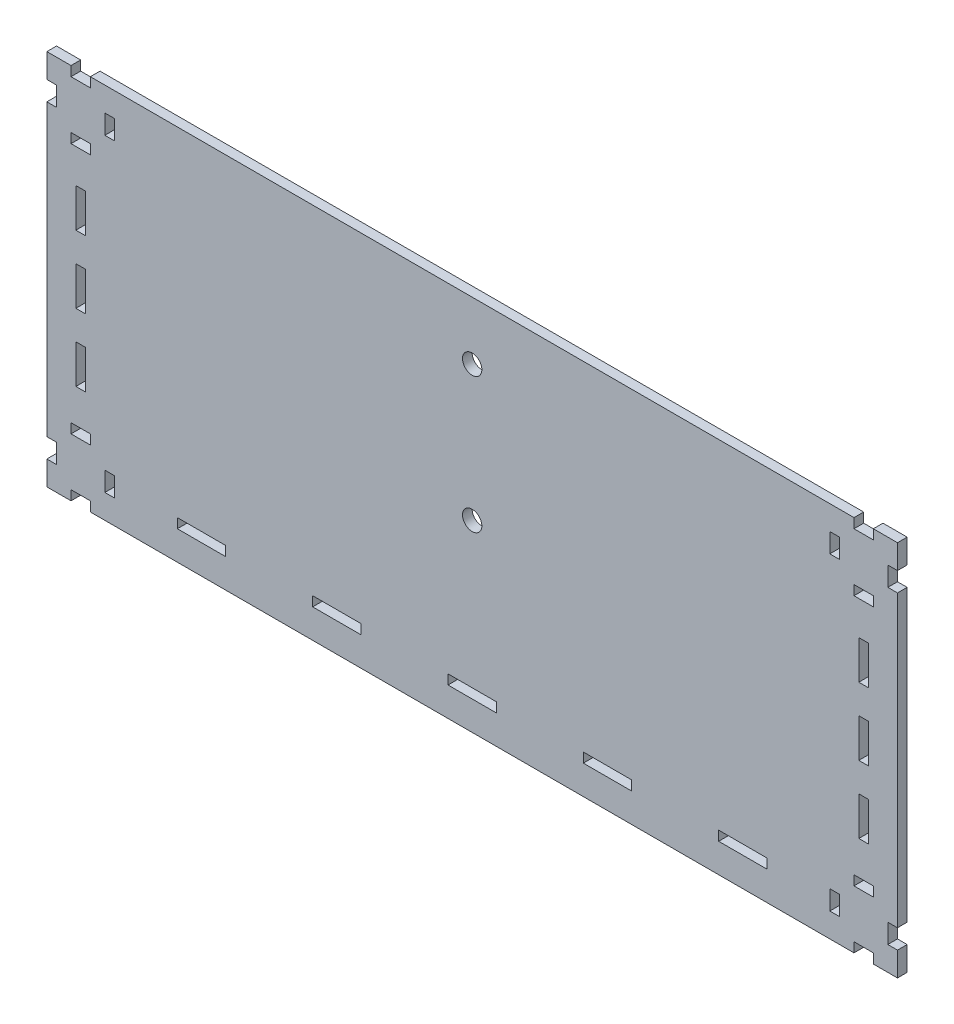
SolidWorks part; units mm, degrees
ref_plane "Front Plane" through (0, 0, 0) normal (0, 0, 1) x (1, 0, 0)
ref_plane "Top Plane" through (0, 0, 0) normal (0, 1, 0) x (1, 0, 0)
ref_plane "Right Plane" through (0, 0, 0) normal (1, 0, 0) x (0, 0, -1)
sketch "Sketch1" plane through (0, 0, 0) normal (0, 0, 1) x (1, 0, 0)
  line L0 (-225, 5) -> (-225, 67.9195) construction
  line L9 (0, 0) -> (-450, 0) construction
  line L10 (0, 0) -> (0, 200) construction
  line L11 (0, 200) -> (-17.5, 200) construction
  line L12 (-450, 0) -> (-450, 200) construction
  line L13 (-5, 5) -> (-17.5, 5)
  line L14 (-5, 5) -> (-5, 17.5)
  line L15 (-5, 200) -> (-17.5, 200)
  line L16 (-445, 5) -> (-445, 17.5)
  line L17 (-17.5, 35) -> (-27.5, 35)
  line L18 (-17.5, 35) -> (-17.5, 40)
  line L19 (-17.5, 40) -> (-27.5, 40)
  line L20 (-27.5, 35) -> (-27.5, 40)
  line L22 (-17.5, 5) -> (-17.5, 10)
  line L23 (-17.5, 10) -> (-27.5, 10)
  line L24 (-27.5, 5) -> (-27.5, 10)
  line L25 (-5, 17.5) -> (-10, 17.5)
  line L27 (-5, 27.5) -> (-10, 27.5)
  line L28 (-10, 17.5) -> (-10, 27.5)
  line L29 (-35.0003, 17.5) -> (-40, 17.5)
  line L30 (-35.0003, 17.5) -> (-35.0003, 27.5)
  line L31 (-35.0003, 27.5) -> (-40, 27.5)
  line L32 (-40, 17.5) -> (-40, 27.5)
  line L33 (-5, 102.5) -> (-45.4791, 102.5) construction
  line L34 (-410, 17.5) -> (-410, 27.5)
  line L35 (-414.9997, 27.5) -> (-410, 27.5)
  line L36 (-414.9997, 17.5) -> (-414.9997, 27.5)
  line L37 (-414.9997, 17.5) -> (-410, 17.5)
  line L38 (-440, 17.5) -> (-440, 27.5)
  line L39 (-445, 27.5) -> (-440, 27.5)
  line L41 (-445, 17.5) -> (-440, 17.5)
  line L42 (-422.5, 5) -> (-422.5, 10)
  line L43 (-432.5, 10) -> (-422.5, 10)
  line L44 (-432.5, 5) -> (-432.5, 10)
  line L46 (-422.5, 35) -> (-422.5, 40)
  line L47 (-432.5, 40) -> (-422.5, 40)
  line L48 (-432.5, 35) -> (-432.5, 40)
  line L49 (-432.5, 35) -> (-422.5, 35)
  line L50 (-432.5, 170) -> (-422.5, 170)
  line L51 (-432.5, 170) -> (-432.5, 165)
  line L52 (-432.5, 165) -> (-422.5, 165)
  line L53 (-422.5, 170) -> (-422.5, 165)
  line L55 (-432.5, 200) -> (-432.5, 195)
  line L56 (-432.5, 195) -> (-422.5, 195)
  line L57 (-422.5, 200) -> (-422.5, 195)
  line L58 (-445, 187.5) -> (-440, 187.5)
  line L60 (-445, 177.5) -> (-440, 177.5)
  line L61 (-440, 187.5) -> (-440, 177.5)
  line L62 (-414.9997, 187.5) -> (-410, 187.5)
  line L63 (-414.9997, 187.5) -> (-414.9997, 177.5)
  line L64 (-414.9997, 177.5) -> (-410, 177.5)
  line L65 (-410, 187.5) -> (-410, 177.5)
  line L66 (0, 205) -> (-450, 205) construction
  line L67 (-40, 187.5) -> (-40, 177.5)
  line L68 (-35.0003, 177.5) -> (-40, 177.5)
  line L69 (-35.0003, 187.5) -> (-35.0003, 177.5)
  line L70 (-35.0003, 187.5) -> (-40, 187.5)
  line L71 (-10, 187.5) -> (-10, 177.5)
  line L72 (-5, 177.5) -> (-10, 177.5)
  line L73 (-5, 187.5) -> (-10, 187.5)
  line L74 (-27.5, 200) -> (-27.5, 195)
  line L75 (-17.5, 195) -> (-27.5, 195)
  line L76 (-17.5, 200) -> (-17.5, 195)
  line L77 (-27.5, 170) -> (-27.5, 165)
  line L78 (-17.5, 165) -> (-27.5, 165)
  line L79 (-17.5, 170) -> (-17.5, 165)
  line L80 (-17.5, 170) -> (-27.5, 170)
  line L81 (-5, 187.5) -> (-5, 200)
  line L82 (-27.5, 200) -> (-422.5, 200) construction
  line L83 (-27.5, 200) -> (-422.5, 200)
  line L84 (-445, 187.5) -> (-445, 200)
  line L85 (-432.5, 200) -> (-450, 200) construction
  line L86 (-432.5, 200) -> (-445, 200)
  line L87 (-445, 27.5) -> (-445, 177.5)
  line L88 (-432.5, 5) -> (-445, 5)
  line L89 (-27.5, 5) -> (-422.5, 5)
  line L90 (-5, 27.5) -> (-5, 177.5)
  line L103 (-430, 57.5) -> (-430, 77.5)
  line L104 (-430, 77.5) -> (-425, 77.5)
  line L105 (-425, 77.5) -> (-425, 57.5)
  line L106 (-425, 57.5) -> (-430, 57.5)
  line L107 (-430, 92.5) -> (-430, 112.5)
  line L108 (-430, 112.5) -> (-425, 112.5)
  line L109 (-425, 112.5) -> (-425, 92.5)
  line L110 (-425, 92.5) -> (-430, 92.5)
  line L111 (-430, 127.5) -> (-430, 147.5)
  line L112 (-430, 147.5) -> (-425, 147.5)
  line L113 (-425, 147.5) -> (-425, 127.5)
  line L114 (-425, 127.5) -> (-430, 127.5)
  line L115 (-25, 127.5) -> (-20, 127.5)
  line L116 (-25, 147.5) -> (-25, 127.5)
  line L117 (-20, 147.5) -> (-25, 147.5)
  line L118 (-20, 127.5) -> (-20, 147.5)
  line L119 (-25, 92.5) -> (-20, 92.5)
  line L120 (-25, 112.5) -> (-25, 92.5)
  line L121 (-20, 112.5) -> (-25, 112.5)
  line L122 (-20, 92.5) -> (-20, 112.5)
  line L123 (-25, 57.5) -> (-20, 57.5)
  line L124 (-25, 77.5) -> (-25, 57.5)
  line L125 (-20, 77.5) -> (-25, 77.5)
  line L126 (-20, 57.5) -> (-20, 77.5)
  line L147 (-377.5, 25) -> (-352.5, 25)
  line L148 (-352.5, 25) -> (-352.5, 20)
  line L149 (-352.5, 20) -> (-377.5, 20)
  line L150 (-377.5, 20) -> (-377.5, 25)
  line L151 (-307.5, 25) -> (-282.5, 25)
  line L152 (-282.5, 25) -> (-282.5, 20)
  line L153 (-282.5, 20) -> (-307.5, 20)
  line L154 (-307.5, 20) -> (-307.5, 25)
  line L155 (-237.5, 25) -> (-212.5, 25)
  line L156 (-212.5, 25) -> (-212.5, 20)
  line L157 (-212.5, 20) -> (-237.5, 20)
  line L158 (-237.5, 20) -> (-237.5, 25)
  line L159 (-167.5, 25) -> (-142.5, 25)
  line L160 (-142.5, 25) -> (-142.5, 20)
  line L161 (-142.5, 20) -> (-167.5, 20)
  line L162 (-167.5, 20) -> (-167.5, 25)
  line L163 (-97.5, 25) -> (-72.5, 25)
  line L164 (-72.5, 25) -> (-72.5, 20)
  line L165 (-72.5, 20) -> (-97.5, 20)
  line L166 (-97.5, 20) -> (-97.5, 25)
  circle A1 centre (-225, 170) radius 5
  circle A2 centre (-225, 100) radius 5
  point P8 (0, 100)
  dimension "D3" = 10
  dimension "D17" = 10
  dimension "D18" = 30
  dimension "D1" = 5
  dimension "D2" = 5
  dimension "D4" = 5
  dimension "D5" = 10
  dimension "D6" = 5
  dimension "D7" = 10
  dimension "D8" = 25
  dimension "D9" = 10
  dimension "D10" = 5
  dimension "D11" = 12.5
  dimension "D12" = 12.5
  dimension "D13" = 12.5
  dimension "D14" = 4.9997
  dimension "D15" = 10
  dimension "D16" = 12.5
extrude "Boss-Extrude1" add sketch "Sketch1" along normal blind 5
